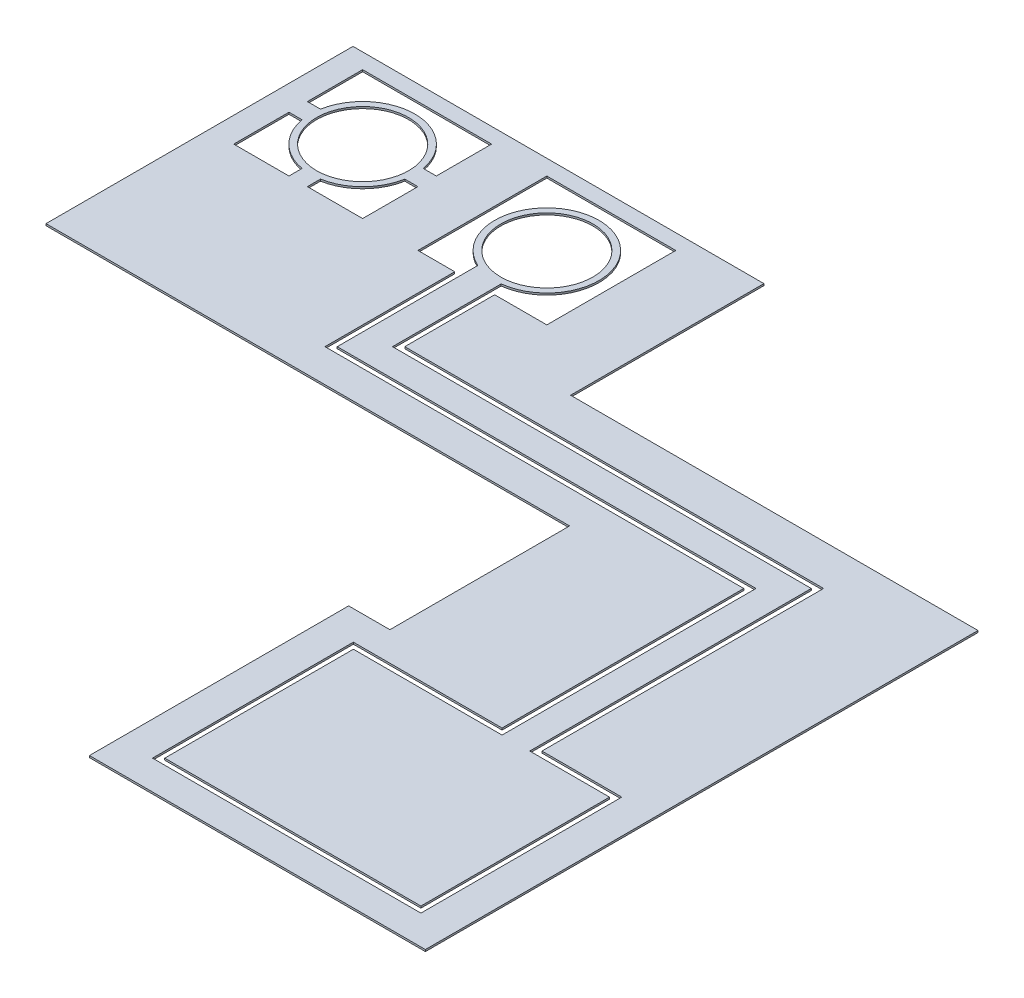
SolidWorks part; units mm, degrees
ref_plane "Front Plane" through (0, 0, 0) normal (0, 0, 1) x (1, 0, 0)
ref_plane "Top Plane" through (0, 0, 0) normal (0, 1, 0) x (1, 0, 0)
ref_plane "Right Plane" through (0, 0, 0) normal (1, 0, 0) x (0, 0, -1)
sketch "Sketch1" plane through (0, 0, 0) normal (0, 1, 0) x (1, 0, 0)
  line L0 (0, 0) -> (0, 5)
  line L1 (0, 5) -> (6.692, 5)
  line L2 (6.692, 5) -> (6.692, 1.851)
  line L3 (6.692, 1.851) -> (13.328, 1.851)
  line L4 (13.328, 1.851) -> (13.328, -7.149)
  line L5 (13.328, -7.149) -> (7.856, -7.149)
  line L6 (7.856, -7.149) -> (7.856, -2.927)
  line L7 (7.856, -2.927) -> (8.528, -2.927)
  line L8 (8.528, -2.927) -> (8.528, 0)
  line L9 (8.528, 0) -> (0, 0)
  line L11 (0.407, 4.75) -> (2.507, 4.75)
  line L12 (0.407, 4.75) -> (0.407, 2.65)
  line L13 (0.407, 2.65) -> (2.507, 2.65)
  line L14 (2.507, 4.75) -> (2.507, 2.65)
  line L15 (3.407, 4.75) -> (5.507, 4.75)
  line L16 (3.407, 4.75) -> (3.407, 2.65)
  line L17 (3.407, 2.65) -> (5.507, 2.65)
  line L18 (5.507, 4.75) -> (5.507, 2.65)
  dimension "D1" = 5
  dimension "D2" = 6.692
  dimension "D3" = 9
  dimension "D4" = 5.472
  dimension "D5" = 8.528
  dimension "D6" = 2.927
  dimension "D7" = 0.672
  dimension "D8" = 4.222
  dimension "D9" = 2.1
  dimension "D10" = 2.1
  dimension "D11" = 2.1
  dimension "D12" = 2.1
  dimension "D13" = 0.407
  dimension "D14" = 0.25
  dimension "D15" = 0.25
  dimension "D16" = 0.9
extrude "Boss-Extrude1" add sketch "Sketch1" along normal blind 0.03
sketch "Sketch2" plane through (0, 0.03, 0) normal (0, 1, 0) x (1, 0, 0)
  line L0 (4.107, 2.65) -> (4.107, 0.636)
  line L1 (3.407, 2.65) -> (5.507, 2.65) construction
  line L2 (4.107, 0.636) -> (10.928, 0.636)
  line L3 (10.928, 0.636) -> (10.928, -3.5)
  line L4 (10.928, -3.5) -> (8.506, -3.5)
  line L5 (8.506, -3.5) -> (8.506, -6.572)
  line L6 (8.506, -6.572) -> (12.678, -6.572)
  line L7 (12.678, -6.572) -> (12.678, -3.5)
  line L8 (12.678, -3.5) -> (11.378, -3.5)
  line L9 (11.378, -3.5) -> (11.378, 1.086)
  line L10 (11.378, 1.086) -> (4.557, 1.086)
  line L11 (4.557, 1.086) -> (4.557, 2.65)
  line L13 (7.856, -7.149) -> (13.328, -7.149) construction
  line L14 (7.856, -2.927) -> (7.856, -7.149) construction
  line L16 (3.407, 4.75) -> (3.407, 2.65) construction
  line L19 (4.657, 1.186) -> (4.657, 2.65)
  line L20 (11.478, 1.186) -> (4.657, 1.186)
  line L21 (11.478, -3.4) -> (11.478, 1.186)
  line L22 (12.778, -3.4) -> (11.478, -3.4)
  line L23 (12.778, -6.672) -> (12.778, -3.4)
  line L24 (8.406, -6.672) -> (12.778, -6.672)
  line L25 (8.406, -3.4) -> (8.406, -6.672)
  line L26 (10.828, -3.4) -> (8.406, -3.4)
  line L27 (10.828, 0.536) -> (10.828, -3.4)
  line L28 (4.007, 0.536) -> (10.828, 0.536)
  line L29 (4.007, 2.65) -> (4.007, 0.536)
  line L30 (4.107, 2.65) -> (4.007, 2.65)
  line L31 (4.557, 2.65) -> (4.657, 2.65)
  line L32 (4.657, 1.186) -> (4.657, 2.75) construction
  line L33 (4.007, 2.75) -> (4.657, 2.75) construction
  line L34 (4.007, 2.75) -> (4.007, 0.536) construction
  line L35 (4.107, 2.65) -> (4.557, 2.65) construction
  dimension "D1" = 0.45
  dimension "D2" = 0.45
  dimension "D3" = 0.45
  dimension "D4" = 3.072
  dimension "D5" = 4.172
  dimension "D6" = 0
  dimension "D7" = 0.577
  dimension "D8" = 0.65
  dimension "D9" = 1.3
  dimension "D10" = 4.586
  dimension "D11" = 0.7
  dimension "D12" = 0.1
extrude "Cut-Extrude1" cut sketch "Sketch2" against normal through all both
sketch "Sketch3" plane through (0, 0.03, 0) normal (0, 1, 0) x (1, 0, 0)
  line L0 (5.507, 4.75) -> (3.407, 4.75) construction
  line L1 (4.107, 2.65) -> (4.557, 2.65)
  line L2 (4.107, 2.65) -> (4.107, 2.9254)
  line L4 (4.557, 2.65) -> (4.557, 2.8559)
  line L5 (5.507, 2.65) -> (5.507, 4.75) construction
  arc A0 (4.557, 2.8559) -> (4.107, 2.9254) centre (4.457, 3.7) ccw
  point P9 (4.457, 4.75)
  point P12 (5.507, 3.7)
  dimension "D3" = 1.7
  dimension "D4" = 0
  dimension "D5" = 0
extrude "Boss-Extrude2" add sketch "Sketch3" against normal up to surface (0.03 mm away) up to face at (8.6923, 0, 1.5333)
sketch "Sketch4" plane through (0, 0.03, 0) normal (0, 1, 0) x (1, 0, 0)
  line L0 (2.507, 4.75) -> (0.407, 4.75) construction
  line L1 (0.407, 2.65) -> (2.507, 2.65) construction
  line L2 (2.507, 2.65) -> (2.507, 4.75) construction
  line L3 (1.307, 2.65) -> (1.607, 2.65)
  line L4 (1.307, 2.65) -> (1.307, 2.8633)
  line L6 (1.607, 2.65) -> (1.607, 2.8633)
  line L7 (2.507, 3.55) -> (2.2937, 3.55)
  line L8 (2.507, 3.55) -> (2.507, 3.85)
  line L9 (2.507, 3.85) -> (2.2937, 3.85)
  line L11 (0.407, 4.75) -> (0.407, 2.65) construction
  line L12 (0.407, 3.85) -> (0.6203, 3.85)
  line L13 (0.407, 3.85) -> (0.407, 3.55)
  line L14 (0.407, 3.55) -> (0.6203, 3.55)
  arc A0 (1.607, 2.8633) -> (2.2937, 3.55) centre (1.457, 3.7) ccw
  arc A1 (2.2937, 3.85) -> (0.6203, 3.85) centre (1.457, 3.7) ccw
  arc A2 (0.6203, 3.55) -> (1.307, 2.8633) centre (1.457, 3.7) ccw
  point P4 (1.457, 4.75)
  point P7 (1.457, 2.65)
  point P24 (1.457, 2.65)
  point P25 (2.507, 3.7)
  point P26 (0.407, 3.7)
  dimension "D1" = 1.7
  dimension "D2" = 1.05
  dimension "D3" = 0
  dimension "D4" = 0.3
  dimension "D5" = 0
  dimension "D6" = 0.3
  dimension "D8" = 0
  dimension "D9" = 0
extrude "Boss-Extrude3" add sketch "Sketch4" against normal up to surface (0.03 mm away) up to face at (7.6335, 0, 0.2125)
sketch "Sketch5" plane through (0, 0.03, 0) normal (0, 1, 0) x (1, 0, 0)
  circle A0 centre (1.457, 3.7) radius 0.75
  circle A1 centre (4.457, 3.7) radius 0.75
  dimension "D1" = 1.5
  dimension "D2" = 1.5
extrude "Cut-Extrude2" cut sketch "Sketch5" against normal through all both
